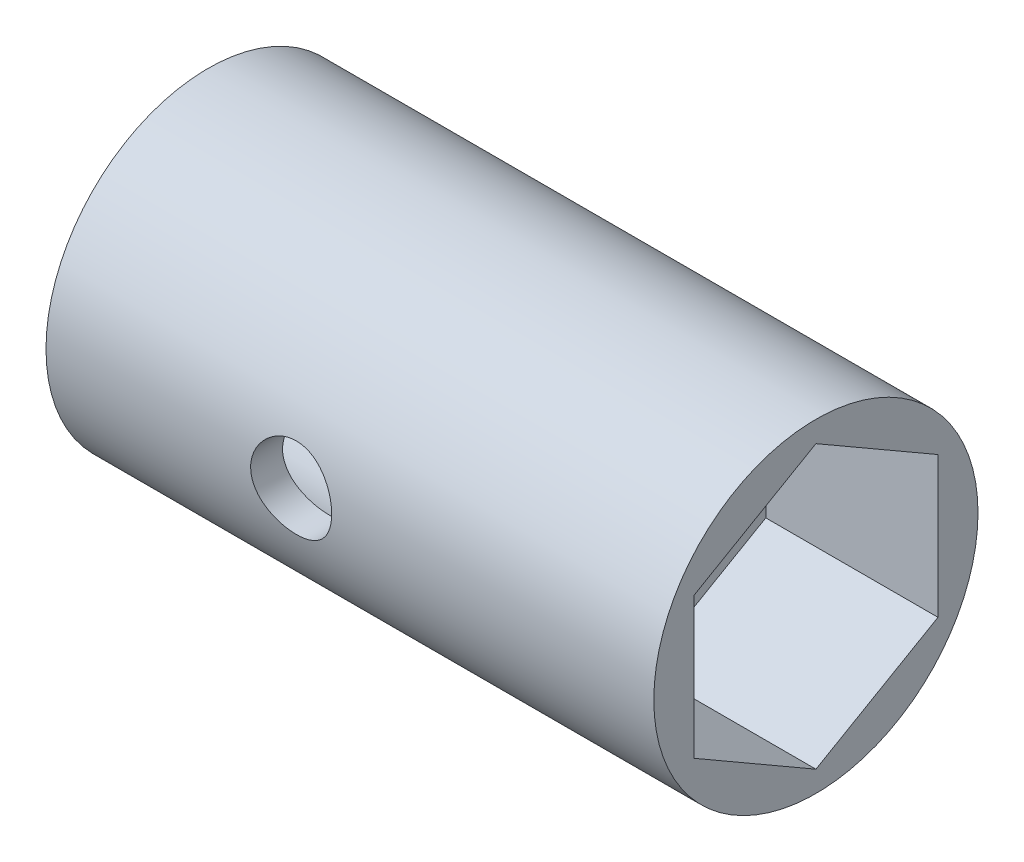
SolidWorks part; units mm, degrees
ref_plane "Alzado" through (0, 0, 0) normal (0, 0, 1) x (1, 0, 0)
ref_plane "Planta" through (0, 0, 0) normal (0, 1, 0) x (1, 0, 0)
ref_plane "Vista lateral" through (0, 0, 0) normal (1, 0, 0) x (0, 0, -1)
sketch "Croquis1" plane through (0, 0, 0) normal (1, 0, 0) x (0, 0, -1)
  line L1 (0, -6.9282) -> (6, -3.4641) construction
  line L2 (6, -3.4641) -> (6, 3.4641) construction
  line L3 (6, 3.4641) -> (0, 6.9282) construction
  line L4 (0, 6.9282) -> (-6, 3.4641) construction
  line L5 (-6, 3.4641) -> (-6, -3.4641) construction
  line L6 (-6, -3.4641) -> (0, -6.9282) construction
  circle A0 centre (0, 0) radius 6.4 construction
  circle A1 centre (0, 0) radius 6 construction
  circle A2 centre (0, 0) radius 8
  dimension "D2" = 12.8
  dimension "D3" = 16
  dimension "D1" = 12
extrude "Saliente-Extruir1" add sketch "Croquis1" along normal blind 20
sketch "Croquis2" plane through (20, 0, 0) normal (1, 0, 0) x (0, 0, -1)
  line L1 (0, -6.9571) -> (6.025, -3.4785)
  line L2 (6.025, -3.4785) -> (6.025, 3.4785)
  line L3 (6.025, 3.4785) -> (0, 6.9571)
  line L4 (0, 6.9571) -> (-6.025, 3.4785)
  line L5 (-6.025, 3.4785) -> (-6.025, -3.4785)
  line L6 (-6.025, -3.4785) -> (0, -6.9571)
  circle A0 centre (0, 0) radius 6.025 construction
  dimension "D1" = 12.05
extrude "Cortar-Extruir1" cut sketch "Croquis2" against normal blind 8.5
sketch "Croquis3" plane through (0, 0, 0) normal (-1, 0, 0) x (0, 0, 1)
  circle A0 centre (0, 0) radius 6.425
  dimension "D1" = 12.85
extrude "Cortar-Extruir2" cut sketch "Croquis3" against normal blind 9
sketch "Croquis4" plane through (9, 0, 0) normal (-1, 0, 0) x (0, 0, 1)
  circle A0 centre (0, 0) radius 2
  dimension "D1" = 4
extrude "Cortar-Extruir3" cut sketch "Croquis4" against normal up to next
sketch "Croquis5" plane through (0, 0, 0) normal (0, 0, 1) x (1, 0, 0)
  circle A0 centre (2.1, 0) radius 2
  dimension "D1" = 4
  dimension "D2" = 2.1
extrude "Cortar-Extruir4" cut sketch "Croquis5" against normal through all and the other way blind 9
sketch "Croquis6" plane through (0, 0, 0) normal (-1, 0, 0) x (0, 0, 1)
  circle A0 centre (0, 0) radius 6.425 construction
  circle A1 centre (0, 0) radius 8
  circle A2 centre (0, 0) radius 8
  circle A3 centre (0, 0) radius 6.425
  dimension "D1" = 0
extrude "Saliente-Extruir2" add sketch "Croquis6" along normal blind 10
equation "\"D1@Croquis2\" = 12 + \"tolerancia\""
equation "\"D1@Croquis3\" = 12.8 + \"tolerancia\""
equation "\"tolerancia\"= 0.05'pla"
